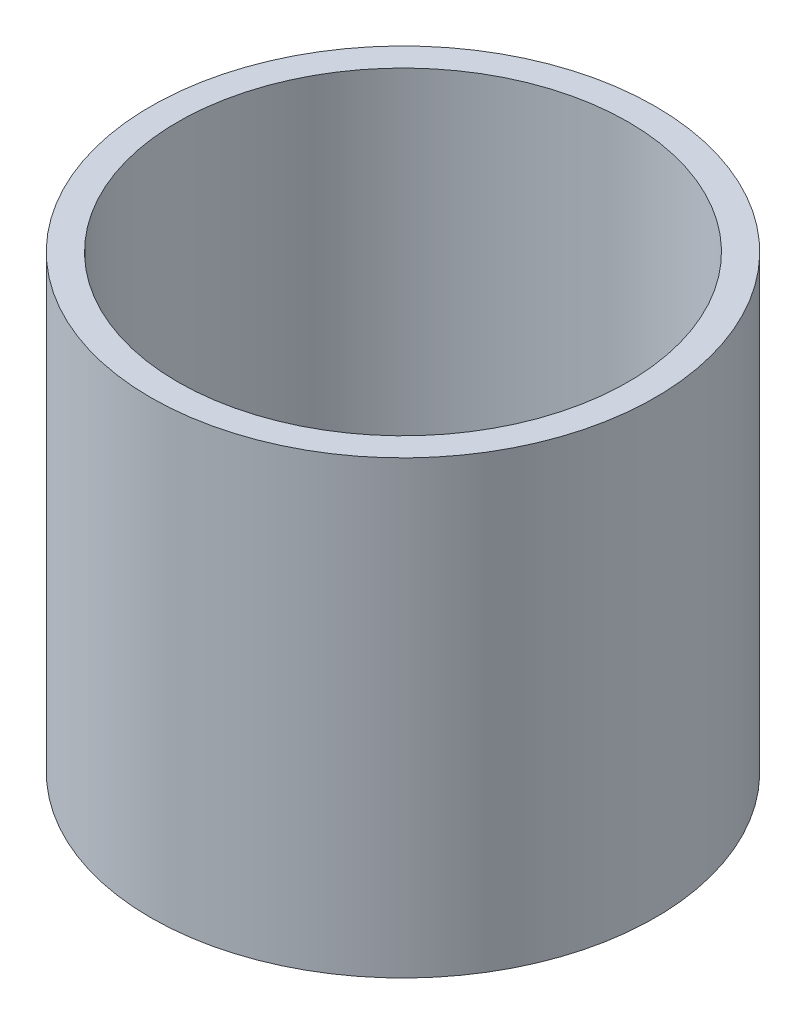
SolidWorks part; units mm, degrees
ref_plane "Front Plane" through (0, 0, 0) normal (0, 0, 1) x (1, 0, 0)
ref_plane "Top Plane" through (0, 0, 0) normal (0, 1, 0) x (1, 0, 0)
ref_plane "Right Plane" through (0, 0, 0) normal (1, 0, 0) x (0, 0, -1)
sketch "Sketch1" plane through (0, 0, 0) normal (0, 1, 0) x (1, 0, 0)
  circle A0 centre (0, 0) radius 2.5
  circle A1 centre (0, 0) radius 2.8
  dimension "D1" = 5
  dimension "D2" = 5.6
extrude "Boss-Extrude1" add sketch "Sketch1" along normal blind 5
